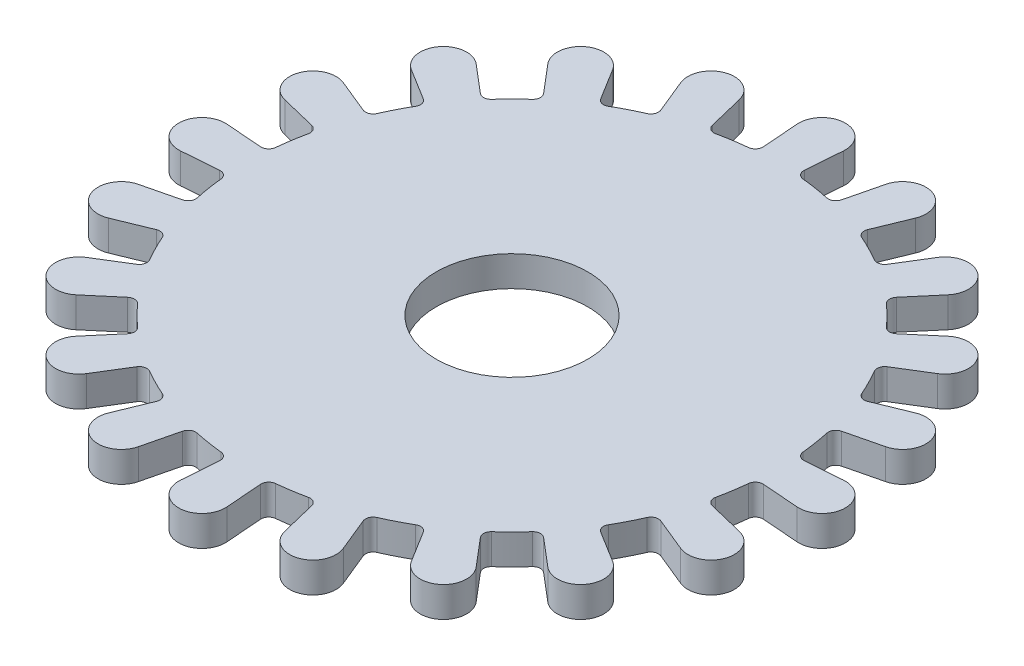
SolidWorks part; units mm, degrees
ref_plane "前视基准面" through (0, 0, 0) normal (0, 0, 1) x (1, 0, 0)
ref_plane "上视基准面" through (0, 0, 0) normal (0, 1, 0) x (1, 0, 0)
ref_plane "右视基准面" through (0, 0, 0) normal (1, 0, 0) x (0, 0, -1)
sketch "草图1" plane through (0, 0, 0) normal (0, 1, 0) x (1, 0, 0)
  circle A0 centre (0, 0) radius 10 construction
  circle A1 centre (0, 0) radius 11 construction
  circle A2 centre (0, 0) radius 8.75
  dimension "D1" = 17.5
  dimension "D2" = 20
  dimension "D3" = 22
extrude "凸台-拉伸1" add sketch "草图1" against normal blind 1
sketch "草图2" plane through (0, 0, 0) normal (0, 1, 0) x (1, 0, 0)
  line L0 (0, 0) -> (0, -11) construction
  line L1 (-0.7653, -10.175) -> (-0.6562, -8.7254)
  line L2 (0.7653, -10.175) -> (0.6563, -8.7254)
  line L3 (0, 0) -> (-0.75, -9.9718) construction
  line L4 (-0.75, -9.9718) -> (0.75, -9.9718) construction
  circle A0 centre (0, 0) radius 11 construction
  circle A1 centre (0, 0) radius 8.75 construction
  arc A2 (-0.7653, -10.175) -> (0.7653, -10.175) centre (0, -10.2326) ccw
  arc A3 (-0.6562, -8.7254) -> (0.6563, -8.7254) centre (0, 0) ccw
  circle A4 centre (0, 0) radius 10 construction
  dimension "D1" = 1.5
extrude "凸台-拉伸2" add sketch "草图2" against normal up to surface (1 mm away) up to face at (0, -1, 8.75)
sketch "草图3" plane through (0, 0, 0) normal (0, 1, 0) x (1, 0, 0)
  circle A0 centre (0, 0) radius 2.5
  dimension "D1" = 5
extrude "切除-拉伸1" cut sketch "草图3" against normal through all
pattern_circular "阵列(圆周)1" count 20 over 360 about axis through (0, 0, 0) along (0, 1, 0) of "凸台-拉伸2"
fillet "圆角1" radius 0.25 40 edges at (2.0722, -0.5, 8.5011) (3.3204, -0.5, 8.0955) (4.5977, -0.5, 7.4447) (5.6596, -0.5, 6.6732) (6.6732, -0.5, 5.6596) (7.4447, -0.5, 4.5977) (8.0955, -0.5, 3.3204) (8.5011, -0.5, 2.0722) (8.7254, -0.5, 0.6562) (8.7254, -0.5, -0.6563) (8.5011, -0.5, -2.0722) (8.0955, -0.5, -3.3204) (7.4447, -0.5, -4.5977) (6.6732, -0.5, -5.6596) (5.6596, -0.5, -6.6732) (4.5977, -0.5, -7.4447) (3.3204, -0.5, -8.0955) (2.0722, -0.5, -8.5011) (0.6562, -0.5, -8.7254) (-0.6563, -0.5, -8.7254) (-2.0722, -0.5, -8.5011) (-3.3204, -0.5, -8.0955) (-4.5977, -0.5, -7.4447) (-5.6596, -0.5, -6.6732) (-6.6732, -0.5, -5.6596) (-7.4447, -0.5, -4.5977) (-8.0955, -0.5, -3.3204) (-8.5011, -0.5, -2.0722) (-8.7254, -0.5, -0.6562) (-8.7254, -0.5, 0.6563) (-8.5011, -0.5, 2.0722) (-8.0955, -0.5, 3.3204) (-7.4447, -0.5, 4.5977) (-6.6732, -0.5, 5.6596) (-5.6596, -0.5, 6.6732) (-4.5977, -0.5, 7.4447) (-3.3204, -0.5, 8.0955) (-2.0722, -0.5, 8.5011) (-0.6562, -0.5, 8.7254) (0.6563, -0.5, 8.7254)
sketch "草图4" plane through (0, 0, 0) normal (0, 0, 1) x (1, 0, 0)
  line L0 (0, -1) -> (0, 48) construction
  line L1 (-0.7674, -1) -> (0.7674, -1) construction
  dimension "D1" = 49
